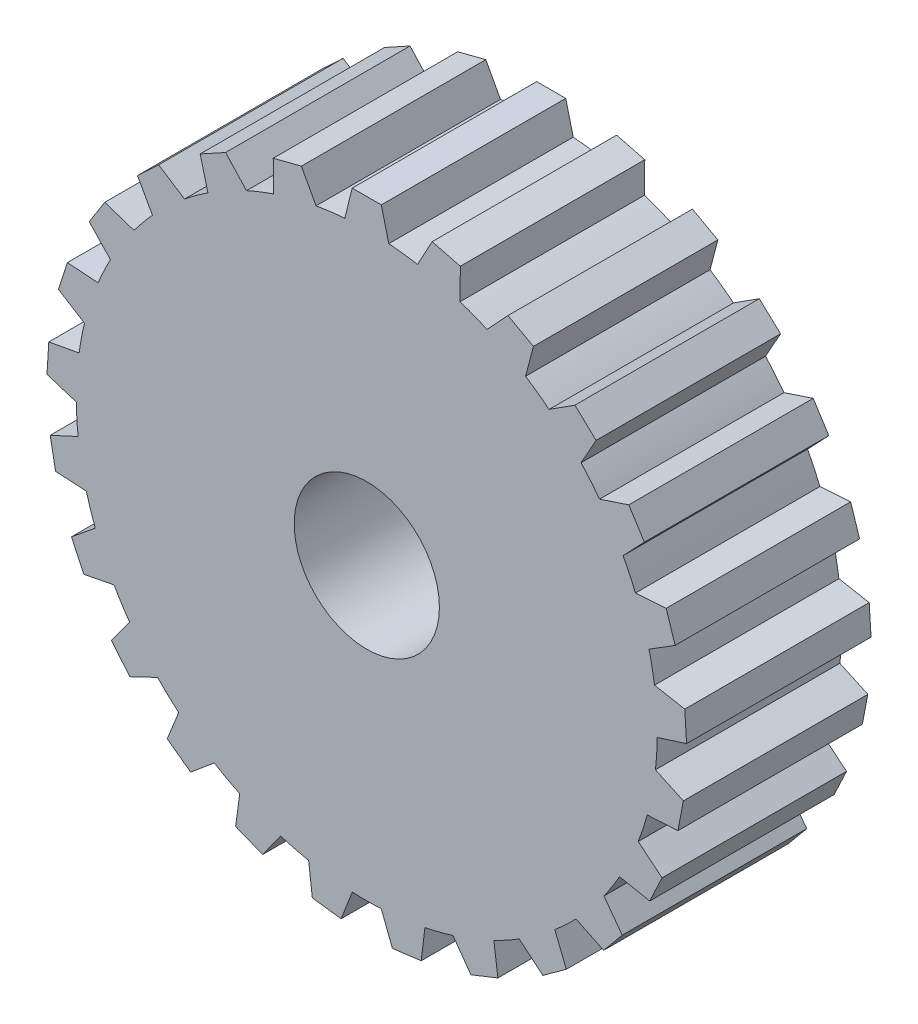
SolidWorks part; units mm, degrees
ref_plane "Front Plane" through (0, 0, 0) normal (0, 0, 1) x (1, 0, 0)
ref_plane "Top Plane" through (0, 0, 0) normal (0, 1, 0) x (1, 0, 0)
ref_plane "Right Plane" through (0, 0, 0) normal (1, 0, 0) x (0, 0, -1)
sketch "Sketch1" plane through (0, 0, 0) normal (0, 0, 1) x (1, 0, 0)
  circle A0 centre (0, 0) radius 10
  circle A1 centre (0, 0) radius 2.5
  dimension "D1" = 20
  dimension "D2" = 5
extrude "Boss-Extrude1" add sketch "Sketch1" along normal blind 6.35
sketch "Sketch2" plane through (0, 0, 6.35) normal (0, 0, 1) x (1, 0, 0)
  line L0 (0, -1000) -> (0, 49000) construction
  line L1 (-0.5, 11) -> (0.5, 11)
  line L2 (0.5, 11) -> (1, 9)
  line L3 (1, 9) -> (-1, 9)
  line L4 (-1, 9) -> (-0.5, 11)
  circle A0 centre (0, 0) radius 10 construction
  point P5 (0, 11)
  point P8 (0, 9)
  dimension "D1" = 2
  dimension "D2" = 1
  dimension "D3" = 9
  dimension "D4" = 11
extrude "Boss-Extrude2" add sketch "Sketch2" against normal blind 6.35
pattern_circular "CirPattern1" count 25 over 360 about axis through (0, 0, 0) along (0, 0, 1) of "Boss-Extrude2"
